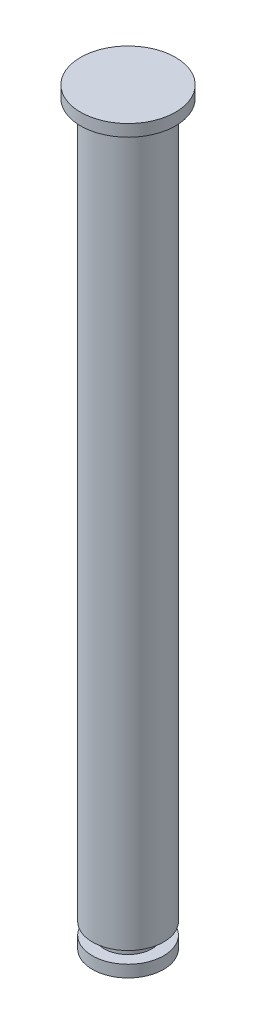
SolidWorks part; units mm, degrees
material "可锻铸铁"
ref_plane "前视基准面" through (0, 0, 0) normal (0, 0, 1) x (1, 0, 0)
ref_plane "上视基准面" through (0, 0, 0) normal (0, 1, 0) x (1, 0, 0)
ref_plane "右视基准面" through (0, 0, 0) normal (1, 0, 0) x (0, 0, -1)
sketch "草图1" plane through (0, 0, 0) normal (1, 0, 0) x (0, 0, -1)
  line L0 (0, 0) -> (0, 45.9858) construction
  line L1 (0, 63) -> (4, 63)
  line L2 (4, 63) -> (4, 62)
  line L3 (4, 62) -> (3, 62)
  line L4 (3, 62) -> (3, 0)
  line L5 (3, 0) -> (0, 0)
  line L6 (0, 0) -> (0, 63)
  dimension "D1" = 3
  dimension "D2" = 1
  dimension "D3" = 1
  dimension "D4" = 62
revolve "旋转1" add sketch "草图1" angle 360 about L0
sketch "草图2" plane through (0, 0, 0) normal (0, 0, 1) x (1, 0, 0)
  line L0 (3, 0) -> (3, 62) construction
  line L1 (3, 35) -> (2, 35)
  line L2 (3, 35) -> (3, 29)
  line L3 (3, 29) -> (2, 29)
  line L4 (2, 35) -> (2, 29)
  line L5 (-3, 32) -> (9.2466, 32) construction
  line L7 (-4, 62) -> (4, 62) construction
  dimension "D1" = 6
  dimension "D2" = 1
  dimension "D3" = 30
extrude "切除-拉伸1" [suppressed] cut sketch "草图2" against normal through all both and the other way through all
sketch "草图4" plane through (0, 0, 0) normal (0, 0, 1) x (1, 0, 0)
  line L0 (3, 0) -> (3, 62) construction
  line L1 (3, 2) -> (2, 2)
  line L2 (3, 2) -> (3, 1)
  line L3 (3, 1) -> (2, 1)
  line L4 (2, 2) -> (2, 1)
  line L5 (-3, 0) -> (3, 0) construction
  line L6 (0, 0) -> (0, 15.1697) construction
  dimension "D1" = 1
  dimension "D2" = 2
  dimension "D3" = 1
revolve "切除-旋转1" cut sketch "草图4" angle 360 about L6
